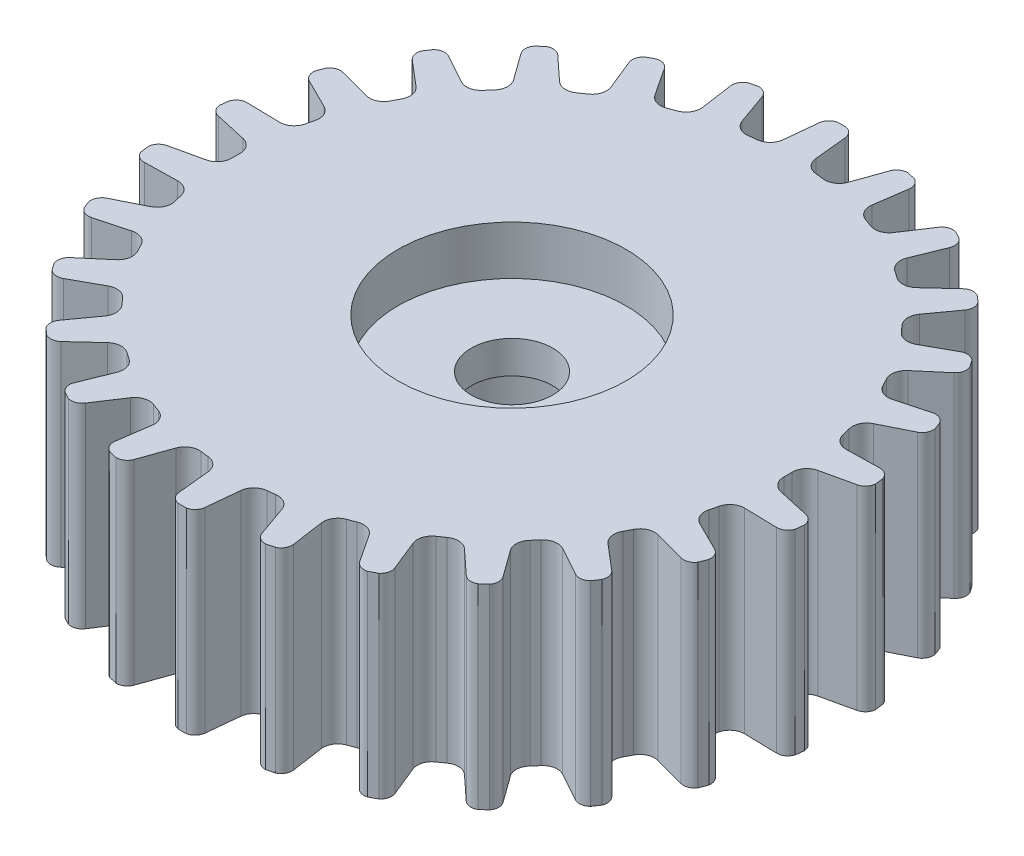
SolidWorks part; units mm, degrees
ref_plane "Front Plane" through (0, 0, 0) normal (0, 0, 1) x (1, 0, 0)
ref_plane "Top Plane" through (0, 0, 0) normal (0, 1, 0) x (1, 0, 0)
ref_plane "Right Plane" through (0, 0, 0) normal (1, 0, 0) x (0, 0, -1)
sketch "Sketch1" plane through (0, 0, 0) normal (0, 1, 0) x (1, 0, 0)
  circle A0 centre (0, 0) radius 2.45
  circle A1 centre (0, 0) radius 10.125
  dimension "D1" = 4.9
  dimension "D2" = 20.25
extrude "Boss-Extrude1" add sketch "Sketch1" along normal blind 6
sketch "Sketch2" plane through (0, 6, 0) normal (0, 1, 0) x (1, 0, 0)
  line L0 (0, 0) -> (0, 10.7871) construction
  line L1 (0.5, 8.825) -> (0.4, 9.825)
  line L2 (-0.5, 8.825) -> (-0.4, 9.825)
  line L3 (1.6265, 8.6882) -> (1.9629, 9.6352)
  line L4 (2.5974, 8.4489) -> (2.7397, 9.4438)
  line L5 (3.6585, 8.0465) -> (4.2117, 8.8855)
  line L6 (4.5439, 7.5818) -> (4.9201, 8.5137)
  line L7 (5.4778, 6.9372) -> (6.2158, 7.6194)
  line L8 (6.2263, 6.274) -> (6.8146, 7.0889)
  line L9 (6.9788, 5.4247) -> (7.8586, 5.9104)
  line L10 (7.5469, 4.6017) -> (8.313, 5.252)
  line L11 (8.0742, 3.5969) -> (9.0447, 3.858)
  line L12 (8.4288, 2.6619) -> (9.3284, 3.11)
  line L13 (8.7004, 1.5601) -> (9.7052, 1.5814)
  line L14 (8.8209, 0.5674) -> (9.8016, 0.7872)
  line L15 (8.8209, -0.5674) -> (9.8016, -0.7872)
  line L16 (8.7004, -1.5601) -> (9.7052, -1.5814)
  line L17 (8.4288, -2.6619) -> (9.3284, -3.11)
  line L18 (8.0742, -3.5969) -> (9.0447, -3.858)
  line L19 (7.5469, -4.6017) -> (8.313, -5.252)
  line L20 (6.9788, -5.4247) -> (7.8586, -5.9104)
  line L21 (6.2263, -6.274) -> (6.8146, -7.0889)
  line L22 (5.4778, -6.9372) -> (6.2158, -7.6194)
  line L23 (4.5439, -7.5818) -> (4.9201, -8.5137)
  line L24 (3.6585, -8.0465) -> (4.2117, -8.8855)
  line L25 (2.5974, -8.4489) -> (2.7397, -9.4438)
  line L26 (1.6265, -8.6882) -> (1.9629, -9.6352)
  line L27 (0.5, -8.825) -> (0.4, -9.825)
  line L28 (-0.5, -8.825) -> (-0.4, -9.825)
  line L29 (-1.6265, -8.6882) -> (-1.9629, -9.6352)
  line L30 (-2.5974, -8.4489) -> (-2.7397, -9.4438)
  line L31 (-3.6585, -8.0465) -> (-4.2117, -8.8855)
  line L32 (-4.5439, -7.5818) -> (-4.9201, -8.5137)
  line L33 (-5.4778, -6.9372) -> (-6.2158, -7.6194)
  line L34 (-6.2263, -6.274) -> (-6.8146, -7.0889)
  line L35 (-6.9788, -5.4247) -> (-7.8586, -5.9104)
  line L36 (-7.5469, -4.6017) -> (-8.313, -5.252)
  line L37 (-8.0742, -3.5969) -> (-9.0447, -3.858)
  line L38 (-8.4288, -2.6619) -> (-9.3284, -3.11)
  line L39 (-8.7004, -1.5601) -> (-9.7052, -1.5814)
  line L40 (-8.8209, -0.5674) -> (-9.8016, -0.7872)
  line L41 (-8.8209, 0.5674) -> (-9.8016, 0.7872)
  line L42 (-8.7004, 1.5601) -> (-9.7052, 1.5814)
  line L43 (-8.4288, 2.6619) -> (-9.3284, 3.11)
  line L44 (-8.0742, 3.5969) -> (-9.0447, 3.858)
  line L45 (-7.5469, 4.6017) -> (-8.313, 5.252)
  line L46 (-6.9788, 5.4247) -> (-7.8586, 5.9104)
  line L47 (-6.2263, 6.274) -> (-6.8146, 7.0889)
  line L48 (-5.4778, 6.9372) -> (-6.2158, 7.6194)
  line L49 (-4.5439, 7.5818) -> (-4.9201, 8.5137)
  line L50 (-3.6585, 8.0465) -> (-4.2117, 8.8855)
  line L51 (-2.5974, 8.4489) -> (-2.7397, 9.4438)
  line L52 (-1.6265, 8.6882) -> (-1.9629, 9.6352)
  circle A0 centre (0, 0) radius 10.125 construction
  circle A1 centre (0, 0) radius 10.125 construction
  arc A2 (0.9, 8.425) -> (1.1424, 8.3956) centre (0, 0) cw
  arc A3 (0.5, 8.825) -> (0.9, 8.425) centre (0.9444, 8.8694) ccw
  arc A4 (0, 10.125) -> (0.4, 9.825) centre (0.0622, 9.7912) cw
  arc A5 (-0.5, 8.825) -> (-0.9, 8.425) centre (-0.9444, 8.8694) cw
  arc A6 (0, 10.125) -> (-0.4, 9.825) centre (-0.0622, 9.7912) ccw
  arc A7 (1.6265, 8.6882) -> (1.1424, 8.3956) centre (1.2056, 8.8377) cw
  arc A8 (2.4231, 9.8308) -> (1.9629, 9.6352) centre (2.2828, 9.5216) ccw
  arc A9 (2.4231, 9.8308) -> (2.7397, 9.4438) centre (2.4035, 9.4918) cw
  arc A10 (2.5974, 8.4489) -> (2.8901, 7.9648) centre (3.0396, 8.3857) ccw
  arc A11 (2.8901, 7.9648) -> (3.1184, 7.8782) centre (0, 0) cw
  arc A12 (3.6585, 8.0465) -> (3.1184, 7.8782) centre (3.2856, 8.2924) cw
  arc A13 (4.7053, 8.9652) -> (4.2117, 8.8855) centre (4.4952, 8.6986) ccw
  arc A14 (4.7053, 8.9652) -> (4.9201, 8.5137) centre (4.6052, 8.6408) cw
  arc A15 (4.5439, 7.5818) -> (4.7122, 7.0417) centre (4.9581, 7.4146) ccw
  arc A16 (4.7122, 7.0417) -> (4.9131, 6.903) centre (0, 0) cw
  arc A17 (5.4778, 6.9372) -> (4.9131, 6.903) centre (5.1746, 7.2652) cw
  arc A18 (6.7141, 7.5787) -> (6.2158, 7.6194) centre (6.4462, 7.3701) ccw
  arc A19 (6.7141, 7.5787) -> (6.8146, 7.0889) centre (6.5393, 7.2876) cw
  arc A20 (6.2263, 6.274) -> (6.2605, 5.7094) centre (6.5885, 6.0126) ccw
  arc A21 (6.2605, 5.7094) -> (6.4224, 5.5266) centre (0, 0) cw
  arc A22 (6.9788, 5.4247) -> (6.4224, 5.5266) centre (6.7629, 5.8157) cw
  arc A23 (8.3327, 5.7517) -> (7.8586, 5.9104) centre (8.0227, 5.6132) ccw
  arc A24 (8.3327, 5.7517) -> (8.313, 5.252) centre (8.0933, 5.5109) cw
  arc A25 (7.5469, 4.6017) -> (7.4449, 4.0453) centre (7.8359, 4.2612) ccw
  arc A26 (7.4449, 4.0453) -> (7.5584, 3.8291) centre (0, 0) cw
  arc A27 (8.0742, 3.5969) -> (7.5584, 3.8291) centre (7.9582, 4.0282) cw
  arc A28 (9.467, 3.5904) -> (9.0447, 3.858) centre (9.1329, 3.5301) ccw
  arc A29 (9.467, 3.5904) -> (9.3284, 3.11) centre (9.177, 3.4139) cw
  arc A30 (8.4288, 2.6619) -> (8.1967, 2.146) centre (8.628, 2.2621) ccw
  arc A31 (8.1967, 2.146) -> (8.2551, 1.909) centre (0, 0) cw
  arc A32 (8.7004, 1.5601) -> (8.2551, 1.909) centre (8.6909, 2.0067) cw
  arc A33 (10.0512, 1.2204) -> (9.7052, 1.5814) centre (9.7123, 1.2419) ccw
  arc A34 (10.0512, 1.2204) -> (9.8016, 0.7872) centre (9.7273, 1.1185) cw
  arc A35 (8.8209, 0.5674) -> (8.4721, 0.1221) centre (8.9186, 0.1315) ccw
  arc A36 (8.4721, 0.1221) -> (8.4721, -0.1221) centre (0, 0) cw
  arc A37 (8.8209, -0.5674) -> (8.4721, -0.1221) centre (8.9186, -0.1315) cw
  arc A38 (10.0512, -1.2204) -> (9.8016, -0.7872) centre (9.7273, -1.1185) ccw
  arc A39 (10.0512, -1.2204) -> (9.7052, -1.5814) centre (9.7123, -1.2419) cw
  arc A40 (8.7004, -1.5601) -> (8.2551, -1.909) centre (8.6909, -2.0067) ccw
  arc A41 (8.2551, -1.909) -> (8.1967, -2.146) centre (0, 0) cw
  arc A42 (8.4288, -2.6619) -> (8.1967, -2.146) centre (8.628, -2.2621) cw
  arc A43 (9.467, -3.5904) -> (9.3284, -3.11) centre (9.177, -3.4139) ccw
  arc A44 (9.467, -3.5904) -> (9.0447, -3.858) centre (9.1329, -3.5301) cw
  arc A45 (8.0742, -3.5969) -> (7.5584, -3.8291) centre (7.9582, -4.0282) ccw
  arc A46 (7.5584, -3.8291) -> (7.4449, -4.0453) centre (0, 0) cw
  arc A47 (7.5469, -4.6017) -> (7.4449, -4.0453) centre (7.8359, -4.2612) cw
  arc A48 (8.3327, -5.7517) -> (8.313, -5.252) centre (8.0933, -5.5109) ccw
  arc A49 (8.3327, -5.7517) -> (7.8586, -5.9104) centre (8.0227, -5.6132) cw
  arc A50 (6.9788, -5.4247) -> (6.4224, -5.5266) centre (6.7629, -5.8157) ccw
  arc A51 (6.4224, -5.5266) -> (6.2605, -5.7094) centre (0, 0) cw
  arc A52 (6.2263, -6.274) -> (6.2605, -5.7094) centre (6.5885, -6.0126) cw
  arc A53 (6.7141, -7.5787) -> (6.8146, -7.0889) centre (6.5393, -7.2876) ccw
  arc A54 (6.7141, -7.5787) -> (6.2158, -7.6194) centre (6.4462, -7.3701) cw
  arc A55 (5.4778, -6.9372) -> (4.9131, -6.903) centre (5.1746, -7.2652) ccw
  arc A56 (4.9131, -6.903) -> (4.7122, -7.0417) centre (0, 0) cw
  arc A57 (4.5439, -7.5818) -> (4.7122, -7.0417) centre (4.9581, -7.4146) cw
  arc A58 (4.7053, -8.9652) -> (4.9201, -8.5137) centre (4.6052, -8.6408) ccw
  arc A59 (4.7053, -8.9652) -> (4.2117, -8.8855) centre (4.4952, -8.6986) cw
  arc A60 (3.6585, -8.0465) -> (3.1184, -7.8782) centre (3.2856, -8.2924) ccw
  arc A61 (3.1184, -7.8782) -> (2.8901, -7.9648) centre (0, 0) cw
  arc A62 (2.5974, -8.4489) -> (2.8901, -7.9648) centre (3.0396, -8.3857) cw
  arc A63 (2.4231, -9.8308) -> (2.7397, -9.4438) centre (2.4035, -9.4918) ccw
  arc A64 (2.4231, -9.8308) -> (1.9629, -9.6352) centre (2.2828, -9.5216) cw
  arc A65 (1.6265, -8.6882) -> (1.1424, -8.3956) centre (1.2056, -8.8377) ccw
  arc A66 (1.1424, -8.3956) -> (0.9, -8.425) centre (0, 0) cw
  arc A67 (0.5, -8.825) -> (0.9, -8.425) centre (0.9444, -8.8694) cw
  arc A68 (0, -10.125) -> (0.4, -9.825) centre (0.0622, -9.7912) ccw
  arc A69 (0, -10.125) -> (-0.4, -9.825) centre (-0.0622, -9.7912) cw
  arc A70 (-0.5, -8.825) -> (-0.9, -8.425) centre (-0.9444, -8.8694) ccw
  arc A71 (-0.9, -8.425) -> (-1.1424, -8.3956) centre (0, 0) cw
  arc A72 (-1.6265, -8.6882) -> (-1.1424, -8.3956) centre (-1.2056, -8.8377) cw
  arc A73 (-2.4231, -9.8308) -> (-1.9629, -9.6352) centre (-2.2828, -9.5216) ccw
  arc A74 (-2.4231, -9.8308) -> (-2.7397, -9.4438) centre (-2.4035, -9.4918) cw
  arc A75 (-2.5974, -8.4489) -> (-2.8901, -7.9648) centre (-3.0396, -8.3857) ccw
  arc A76 (-2.8901, -7.9648) -> (-3.1184, -7.8782) centre (0, 0) cw
  arc A77 (-3.6585, -8.0465) -> (-3.1184, -7.8782) centre (-3.2856, -8.2924) cw
  arc A78 (-4.7053, -8.9652) -> (-4.2117, -8.8855) centre (-4.4952, -8.6986) ccw
  arc A79 (-4.7053, -8.9652) -> (-4.9201, -8.5137) centre (-4.6052, -8.6408) cw
  arc A80 (-4.5439, -7.5818) -> (-4.7122, -7.0417) centre (-4.9581, -7.4146) ccw
  arc A81 (-4.7122, -7.0417) -> (-4.9131, -6.903) centre (0, 0) cw
  arc A82 (-5.4778, -6.9372) -> (-4.9131, -6.903) centre (-5.1746, -7.2652) cw
  arc A83 (-6.7141, -7.5787) -> (-6.2158, -7.6194) centre (-6.4462, -7.3701) ccw
  arc A84 (-6.7141, -7.5787) -> (-6.8146, -7.0889) centre (-6.5393, -7.2876) cw
  arc A85 (-6.2263, -6.274) -> (-6.2605, -5.7094) centre (-6.5885, -6.0126) ccw
  arc A86 (-6.2605, -5.7094) -> (-6.4224, -5.5266) centre (0, 0) cw
  arc A87 (-6.9788, -5.4247) -> (-6.4224, -5.5266) centre (-6.7629, -5.8157) cw
  arc A88 (-8.3327, -5.7517) -> (-7.8586, -5.9104) centre (-8.0227, -5.6132) ccw
  arc A89 (-8.3327, -5.7517) -> (-8.313, -5.252) centre (-8.0933, -5.5109) cw
  arc A90 (-7.5469, -4.6017) -> (-7.4449, -4.0453) centre (-7.8359, -4.2612) ccw
  arc A91 (-7.4449, -4.0453) -> (-7.5584, -3.8291) centre (0, 0) cw
  arc A92 (-8.0742, -3.5969) -> (-7.5584, -3.8291) centre (-7.9582, -4.0282) cw
  arc A93 (-9.467, -3.5904) -> (-9.0447, -3.858) centre (-9.1329, -3.5301) ccw
  arc A94 (-9.467, -3.5904) -> (-9.3284, -3.11) centre (-9.177, -3.4139) cw
  arc A95 (-8.4288, -2.6619) -> (-8.1967, -2.146) centre (-8.628, -2.2621) ccw
  arc A96 (-8.1967, -2.146) -> (-8.2551, -1.909) centre (0, 0) cw
  arc A97 (-8.7004, -1.5601) -> (-8.2551, -1.909) centre (-8.6909, -2.0067) cw
  arc A98 (-10.0512, -1.2204) -> (-9.7052, -1.5814) centre (-9.7123, -1.2419) ccw
  arc A99 (-10.0512, -1.2204) -> (-9.8016, -0.7872) centre (-9.7273, -1.1185) cw
  arc A100 (-8.8209, -0.5674) -> (-8.4721, -0.1221) centre (-8.9186, -0.1315) ccw
  arc A101 (-8.4721, -0.1221) -> (-8.4721, 0.1221) centre (0, 0) cw
  arc A102 (-8.8209, 0.5674) -> (-8.4721, 0.1221) centre (-8.9186, 0.1315) cw
  arc A103 (-10.0512, 1.2204) -> (-9.8016, 0.7872) centre (-9.7273, 1.1185) ccw
  arc A104 (-10.0512, 1.2204) -> (-9.7052, 1.5814) centre (-9.7123, 1.2419) cw
  arc A105 (-8.7004, 1.5601) -> (-8.2551, 1.909) centre (-8.6909, 2.0067) ccw
  arc A106 (-8.2551, 1.909) -> (-8.1967, 2.146) centre (0, 0) cw
  arc A107 (-8.4288, 2.6619) -> (-8.1967, 2.146) centre (-8.628, 2.2621) cw
  arc A108 (-9.467, 3.5904) -> (-9.3284, 3.11) centre (-9.177, 3.4139) ccw
  arc A109 (-9.467, 3.5904) -> (-9.0447, 3.858) centre (-9.1329, 3.5301) cw
  arc A110 (-8.0742, 3.5969) -> (-7.5584, 3.8291) centre (-7.9582, 4.0282) ccw
  arc A111 (-7.5584, 3.8291) -> (-7.4449, 4.0453) centre (0, 0) cw
  arc A112 (-7.5469, 4.6017) -> (-7.4449, 4.0453) centre (-7.8359, 4.2612) cw
  arc A113 (-8.3327, 5.7517) -> (-8.313, 5.252) centre (-8.0933, 5.5109) ccw
  arc A114 (-8.3327, 5.7517) -> (-7.8586, 5.9104) centre (-8.0227, 5.6132) cw
  arc A115 (-6.9788, 5.4247) -> (-6.4224, 5.5266) centre (-6.7629, 5.8157) ccw
  arc A116 (-6.4224, 5.5266) -> (-6.2605, 5.7094) centre (0, 0) cw
  arc A117 (-6.2263, 6.274) -> (-6.2605, 5.7094) centre (-6.5885, 6.0126) cw
  arc A118 (-6.7141, 7.5787) -> (-6.8146, 7.0889) centre (-6.5393, 7.2876) ccw
  arc A119 (-6.7141, 7.5787) -> (-6.2158, 7.6194) centre (-6.4462, 7.3701) cw
  arc A120 (-5.4778, 6.9372) -> (-4.9131, 6.903) centre (-5.1746, 7.2652) ccw
  arc A121 (-4.9131, 6.903) -> (-4.7122, 7.0417) centre (0, 0) cw
  arc A122 (-4.5439, 7.5818) -> (-4.7122, 7.0417) centre (-4.9581, 7.4146) cw
  arc A123 (-4.7053, 8.9652) -> (-4.9201, 8.5137) centre (-4.6052, 8.6408) ccw
  arc A124 (-4.7053, 8.9652) -> (-4.2117, 8.8855) centre (-4.4952, 8.6986) cw
  arc A125 (-3.6585, 8.0465) -> (-3.1184, 7.8782) centre (-3.2856, 8.2924) ccw
  arc A126 (-3.1184, 7.8782) -> (-2.8901, 7.9648) centre (0, 0) cw
  arc A127 (-2.5974, 8.4489) -> (-2.8901, 7.9648) centre (-3.0396, 8.3857) cw
  arc A128 (-2.4231, 9.8308) -> (-2.7397, 9.4438) centre (-2.4035, 9.4918) ccw
  arc A129 (-2.4231, 9.8308) -> (-1.9629, 9.6352) centre (-2.2828, 9.5216) cw
  arc A130 (-1.6265, 8.6882) -> (-1.1424, 8.3956) centre (-1.2056, 8.8377) ccw
  arc A131 (-1.1424, 8.3956) -> (-0.9, 8.425) centre (0, 0) cw
  circle A132 centre (0, 0) radius 11.1781
  point P321 (0, 0)
  dimension "D7" = 26
  dimension "D1" = 0.4
  dimension "D2" = 0.1
  dimension "D3" = 1
  dimension "D4" = 0.3
  dimension "D5" = 0.4
  dimension "D6" = 0.4
extrude "Cut-Extrude1" cut sketch "Sketch2" against normal up to next
sketch "Sketch3" plane through (0, 6, 0) normal (0, 1, 0) x (1, 0, 0)
  circle A0 centre (0, 0) radius 2.45 construction
  circle A1 centre (0, 0) radius 2.45
  circle A2 centre (0, 0) radius 1.25
  dimension "D1" = 2.5
extrude "Boss-Extrude2" add sketch "Sketch3" against normal blind 2.5
sketch "Sketch4" plane through (0, 6, 0) normal (0, 1, 0) x (1, 0, 0)
  circle A0 centre (0, 0) radius 3.5
  dimension "D1" = 7
extrude "Cut-Extrude2" cut sketch "Sketch4" against normal blind 1.5
